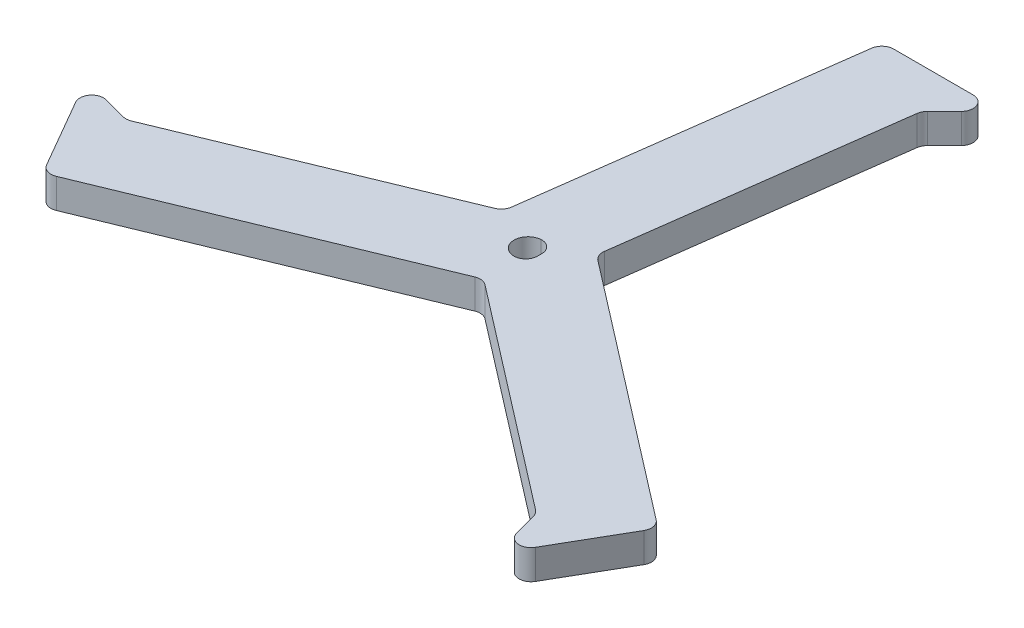
SolidWorks part; units mm, degrees
ref_plane "Front Plane" through (0, 0, 0) normal (0, 0, 1) x (1, 0, 0)
ref_plane "Top Plane" through (0, 0, 0) normal (0, 1, 0) x (1, 0, 0)
ref_plane "Right Plane" through (0, 0, 0) normal (1, 0, 0) x (0, 0, -1)
sketch "Sketch2" plane through (0, 0, 0) normal (0, 1, 0) x (1, 0, 0)
  line L0 (2.5, 1.6583) -> (2.5, -1.6583)
  line L1 (0, 76.2) -> (25.4, 76.2)
  line L2 (0, 0) -> (-8.9803, 8.9803) construction
  line L3 (0, 0) -> (8.9803, 8.9803) construction
  line L4 (0, 0) -> (0, 3) construction
  line L5 (-9.5937, 4.3884) -> (0, 76.2)
  line L6 (25.4, 76.2) -> (16.8134, 67.6134)
  line L7 (16.8134, 67.6134) -> (8.5974, 6.1142)
  line L8 (50.1482, -48.3675) -> (0.9963, -10.5026)
  line L9 (53.2911, -60.097) -> (50.1482, -48.3675)
  line L10 (65.9911, -38.1) -> (53.2911, -60.097)
  line L11 (8.5974, 6.1142) -> (65.9911, -38.1)
  line L12 (-66.9616, -19.2459) -> (-9.5937, 4.3884)
  line L13 (-78.6911, -16.103) -> (-66.9616, -19.2459)
  line L14 (-65.9911, -38.1) -> (-78.6911, -16.103)
  line L15 (0.9963, -10.5026) -> (-65.9911, -38.1)
  arc A0 (2.5, 1.6583) -> (2.5, -1.6583) centre (0, 0) ccw
  circle A1 centre (0, 0) radius 12.7 construction
  point P5 (3, 0)
  point P36 (0, 0)
  dimension "D1" = 6
  dimension "D6" = 25.4
  dimension "D2" = 0.5
  dimension "D3" = 76.2
  dimension "D4" = 90
  dimension "D5" = 25.4
  dimension "D7" = 45
  dimension "D8" = 45
  dimension "D9" = 3
extrude "Boss-Extrude1" add sketch "Sketch2" along normal blind 6.35
fillet "Fillet1" radius 2.54 14 edges at (0, 3.175, -76.2) (25.4, 3.175, -76.2) (16.8134, 3.175, -67.6134) (8.5974, 3.175, -6.1142) (65.9911, 3.175, 38.1) (53.2911, 3.175, 60.097) (50.1482, 3.175, 48.3675) (0.9963, 3.175, 10.5026) (-65.9911, 3.175, 38.1) (-78.6911, 3.175, 16.103) (-66.9616, 3.175, 19.2459) (-9.5937, 3.175, -4.3884) (2.5, 3.175, -1.6583) (2.5, 3.175, 1.6583)
